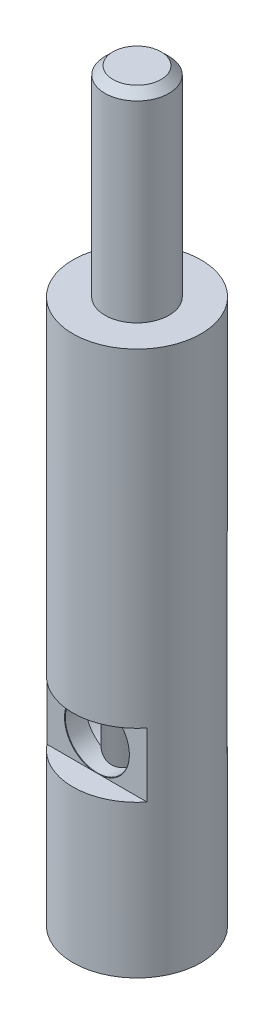
SolidWorks part; units mm, degrees
ref_plane "Front Plane" through (0, 0, 0) normal (0, 0, 1) x (1, 0, 0)
ref_plane "Top Plane" through (0, 0, 0) normal (0, 1, 0) x (1, 0, 0)
ref_plane "Right Plane" through (0, 0, 0) normal (1, 0, 0) x (0, 0, -1)
sketch "Sketch1" plane through (0, 0, 0) normal (0, 1, 0) x (1, 0, 0)
  circle A0 centre (0, 0) radius 4
  dimension "D1" = 8
extrude "Boss-Extrude1" add sketch "Sketch1" along normal blind 34
sketch "Sketch2" plane through (0, 0, 0) normal (0, -1, 0) x (-1, 0, 0)
  circle A0 centre (0, 0) radius 1.6
  point P0 (0, 0)
  dimension "D1" = 3.2
hole_wizard "Ø3.2 (3.2) Diameter Hole3" positions "Sketch2" profile "Sketch3" hole size "Ø3.2" standard "ANSI Metric"
sketch "Sketch3" plane through (0, 0, 0) normal (1, 0, 0) x (0, 0, -1)
  line L0 (0, 0) -> (0, 14.9614)
  line L1 (0, 14.9614) -> (1.6, 14)
  line L2 (1.6, 14) -> (1.6, 0.025)
  line L3 (1.6, 0.025) -> (1.625, 0)
  line L5 (1.625, 0) -> (0, 0)
  line L6 (-1.6, 0.025) -> (-1.625, 0) construction
  line L10 (0, 14.9614) -> (-1.6, 14) construction
  line L11 (0, -6.35) -> (0, 36.5278) construction
  dimension "Hole Dia." = 3.2
  dimension "Hole Depth" = 14
  dimension "Near C'Sink Dia." = 3.25
  dimension "Near C'Sink Angle" = 90
  dimension "Drill Angle" = 118
sketch "Sketch4" plane through (0, 0, 0) normal (1, 0, 0) x (0, 0, -1)
  line L0 (-4, 34) -> (-4, 0) construction
  line L1 (-5.5, 13.5) -> (-2.5, 13.5)
  line L2 (-5.5, 13.5) -> (-5.5, 9.5)
  line L3 (-5.5, 9.5) -> (-2.5, 9.5)
  line L4 (-2.5, 13.5) -> (-2.5, 9.5)
  line L5 (-5.5, 13.5) -> (-2.5, 9.5) construction
  line L6 (-5.5, 9.5) -> (-2.5, 13.5) construction
  line L7 (4, 0) -> (4, 34) construction
  line L8 (2.5, 21.5) -> (5.5, 21.5)
  line L9 (2.5, 21.5) -> (2.5, 9.5)
  line L10 (2.5, 9.5) -> (5.5, 9.5)
  line L11 (5.5, 21.5) -> (5.5, 9.5)
  line L12 (2.5, 21.5) -> (5.5, 9.5) construction
  line L13 (2.5, 9.5) -> (5.5, 21.5) construction
  line L14 (-4, 0) -> (4, 0) construction
  point P0 (-4, 11.5)
  point P7 (4, 15.5)
  dimension "D1" = 9.5
  dimension "D2" = 9.5
  dimension "D3" = 3
  dimension "D4" = 3
  dimension "D5" = 12
  dimension "D6" = 4
extrude "Cut-Extrude1" cut sketch "Sketch4" against normal mid plane 8
sketch "Sketch5" plane through (0, 0, 2.5) normal (0, 0, 1) x (1, 0, 0)
  circle A0 centre (0, 11.5) radius 2
  point P0 (0, 11.5)
  point P5 (0, 11.5)
  point P7 (0, 11.5)
hole_wizard "Ø4.0 (4) Diameter Hole2" positions "Sketch5" profile "Sketch6" hole size "Ø4.0" standard "ANSI Metric"
sketch "Sketch6" plane through (0, 11.5, 2.5) normal (1, 0, 0) x (0, -1, 0)
  line L0 (0, 0) -> (0, 2.5)
  line L1 (0, 2.5) -> (2, 1.2983)
  line L2 (2, 1.2983) -> (2, 0.025)
  line L3 (2, 0.025) -> (2.025, 0)
  line L5 (2.025, 0) -> (0, 0)
  line L6 (-2, 0.025) -> (-2.025, 0) construction
  line L10 (0, 2.5) -> (-2, 1.2983) construction
  line L11 (0, -6.35) -> (0, 107.95) construction
  dimension "Hole Dia." = 4
  dimension "Hole Depth" = 2.5
  dimension "Near C'Sink Dia." = 4.05
  dimension "Near C'Sink Angle" = 90
  dimension "Drill Angle" = 118
sketch "Sketch8" plane through (0, 34, 0) normal (0, 1, 0) x (1, 0, 0)
  circle A0 centre (0, 0) radius 2
  dimension "D1" = 4
extrude "Boss-Extrude2" add sketch "Sketch8" along normal blind 12
sketch "Sketch9" plane through (0, 46, 0) normal (0, 1, 0) x (1, 0, 0)
  circle A0 centre (0, 0) radius 2
extrude "Boss-Extrude3" add sketch "Sketch9" along normal blind 0.5 draft 45
